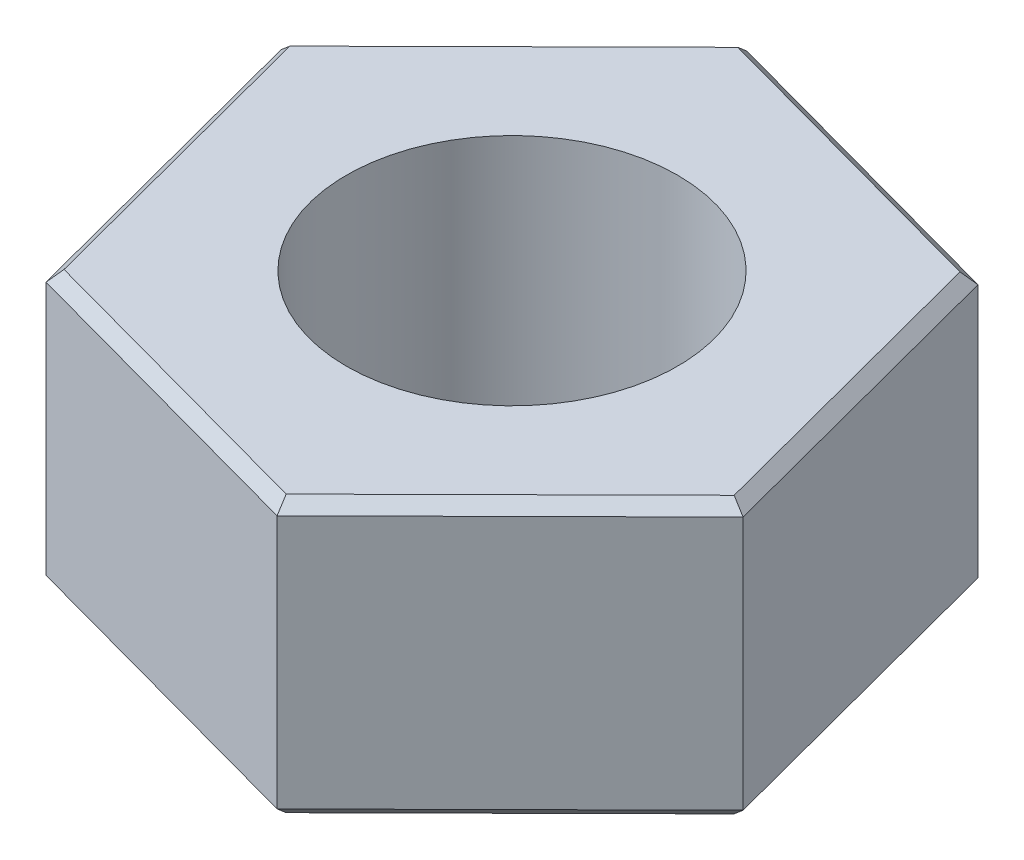
SolidWorks part; units mm, degrees
material "Gray Cast Iron"
ref_plane "Front Plane" through (0, 0, 0) normal (0, 0, 1) x (1, 0, 0)
ref_plane "Top Plane" through (0, 0, 0) normal (0, 1, 0) x (1, 0, 0)
ref_plane "Right Plane" through (0, 0, 0) normal (1, 0, 0) x (0, 0, -1)
sketch "Sketch1" plane through (0, 0, 0) normal (0, 1, 0) x (1, 0, 0)
  line L1 (-4.242, -4.202) -> (1.5181, -5.7747)
  line L2 (1.5181, -5.7747) -> (5.7601, -1.5727)
  line L3 (5.7601, -1.5727) -> (4.242, 4.202)
  line L4 (4.242, 4.202) -> (-1.5181, 5.7747)
  line L5 (-1.5181, 5.7747) -> (-5.7601, 1.5727)
  line L6 (-5.7601, 1.5727) -> (-4.242, -4.202)
  circle A0 centre (0, 0) radius 3
extrude "Boss-Extrude1" add sketch "Sketch1" along normal blind 5
chamfer "Chamfer2" distance 0.2 angle 45 12 edges at (-3.6391, 0, -3.6737) (1.362, 0, -4.9884) (5.001, 0, -1.3147) (3.6391, 0, 3.6737) (-1.362, 0, 4.9884) (-5.001, 0, 1.3147) (1.362, 5, -4.9884) (5.001, 5, -1.3147) (3.6391, 5, 3.6737) (-1.362, 5, 4.9884) (-3.6391, 5, -3.6737) (-5.001, 5, 1.3147)
